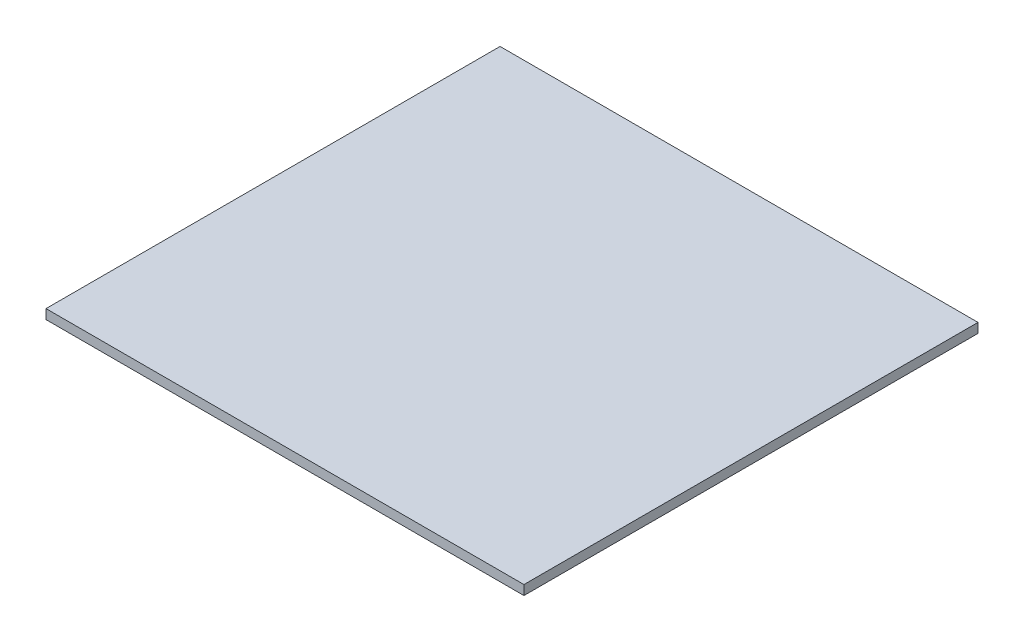
SolidWorks part; units mm, degrees
ref_plane "Front Plane" through (0, 0, 0) normal (0, 0, 1) x (1, 0, 0)
ref_plane "Top Plane" through (0, 0, 0) normal (0, 1, 0) x (1, 0, 0)
ref_plane "Right Plane" through (0, 0, 0) normal (1, 0, 0) x (0, 0, -1)
sketch "Sketch1" plane through (0, 0, 0) normal (0, 1, 0) x (1, 0, 0)
  line L1 (50, -47.5) -> (-50, -47.5)
  line L2 (50, -47.5) -> (50, 47.5)
  line L3 (50, 47.5) -> (-50, 47.5)
  line L4 (-50, -47.5) -> (-50, 47.5)
  line L5 (50, -47.5) -> (-50, 47.5) construction
  line L6 (50, 47.5) -> (-50, -47.5) construction
  point P0 (0, 0)
  dimension "D1" = 95
  dimension "D2" = 100
extrude "Boss-Extrude1" add sketch "Sketch1" along normal mid plane 2
